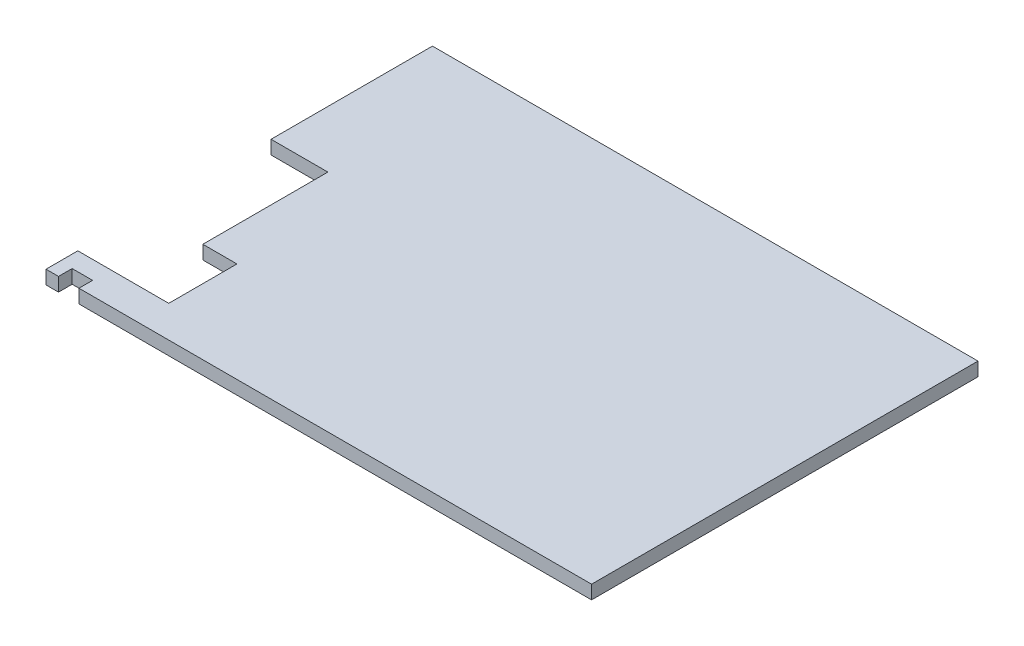
SolidWorks part; units mm, degrees
material "Acrilico TEC"
ref_plane "Front Plane" through (0, 0, 0) normal (0, 0, 1) x (1, 0, 0)
ref_plane "Top Plane" through (0, 0, 0) normal (0, 1, 0) x (1, 0, 0)
ref_plane "Right Plane" through (0, 0, 0) normal (1, 0, 0) x (0, 0, -1)
sketch "Sketch1" plane through (0, 0, 0) normal (0, 1, 0) x (1, 0, 0)
  line L0 (14.5, 4.7967) -> (240, 4.7967)
  line L1 (0, 4.7967) -> (5.5, 4.7967)
  line L2 (0, 103.7967) -> (0, 174.7967)
  line L3 (0, 174.7967) -> (240, 174.7967)
  line L4 (240, 4.7967) -> (240, 174.7967)
  line L6 (5.5, 4.7967) -> (5.5, 10.7967)
  line L7 (18.8044, 18.7967) -> (25, 18.7967)
  line L8 (25, 48.7967) -> (25, 103.7967)
  line L9 (25, 103.7967) -> (0, 103.7967)
  line L10 (25, 18.7967) -> (40, 18.7967)
  line L11 (40, 18.7967) -> (40, 48.7967)
  line L12 (40, 48.7967) -> (25, 48.7967)
  line L13 (0, 4.7967) -> (0, 18.7967)
  line L14 (0, 18.7967) -> (18.8044, 18.7967)
  line L15 (5.5, 10.7967) -> (14.5, 10.7967)
  line L16 (14.5, 4.7967) -> (14.5, 10.7967)
  dimension "D2" = 170
  dimension "D3" = 240
  dimension "D4" = 9
  dimension "D5" = 25
  dimension "D6" = 85
  dimension "D7" = 14
  dimension "D8" = 15
  dimension "D9" = 30
  dimension "D10" = 15
  dimension "D11" = 6.1956
  dimension "D12" = 6
  dimension "D13" = 5.5
extrude "Boss-Extrude1" add sketch "Sketch1" along normal blind 6
